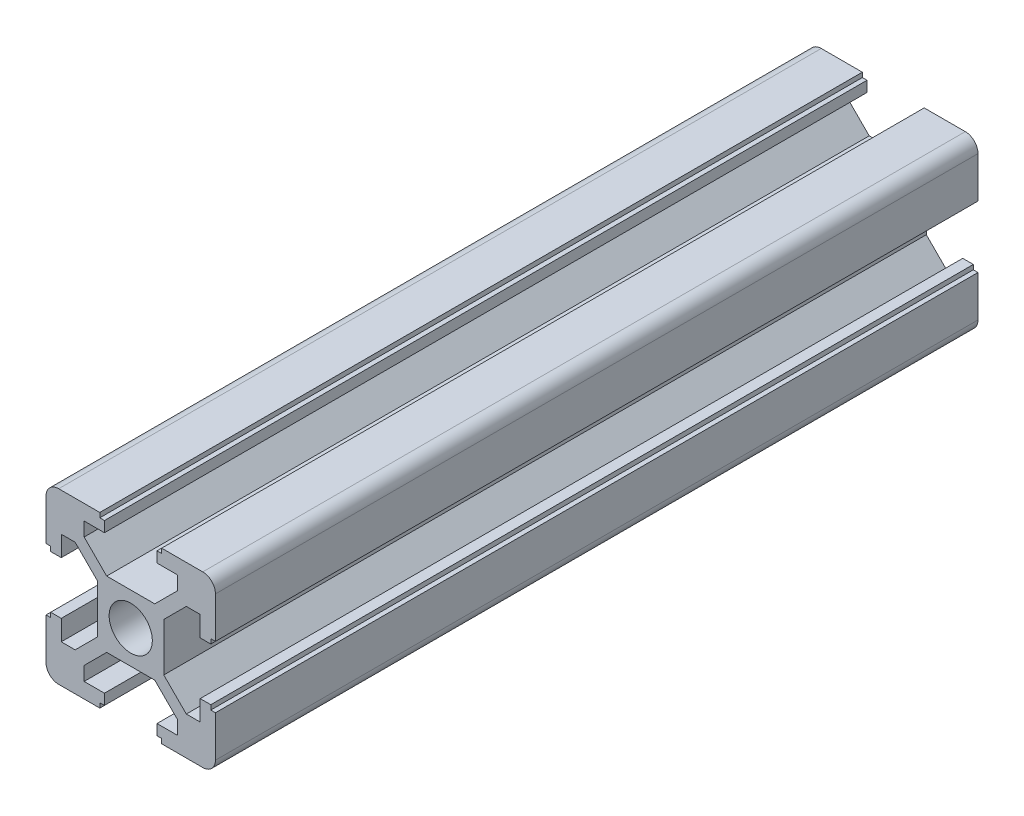
SolidWorks part; units mm, degrees
material "1060 Alloy"
ref_plane "Front Plane" through (0, 0, 0) normal (0, 0, 1) x (1, 0, 0)
ref_plane "Top Plane" through (0, 0, 0) normal (0, 1, 0) x (1, 0, 0)
ref_plane "Right Plane" through (0, 0, 0) normal (1, 0, 0) x (0, 0, -1)
sketch "Sketch2" plane through (0, 0, 0) normal (0, 0, 1) x (1, 0, 0)
  line L0 (-10, 10) -> (-3.65, 10)
  line L7 (-3.65, 10) -> (-3.65, 9.45)
  line L8 (-3.65, 9.45) -> (-3.1, 9.45)
  line L9 (-3.1, 9.45) -> (-3.1, 8.2)
  line L10 (-3.1, 8.2) -> (-5.5, 8.2)
  line L11 (-5.5, 8.2) -> (-5.5, 6.5607)
  line L18 (0, 0) -> (-10, 10) construction
  line L20 (-2.8393, 3.9) -> (-5.5, 6.5607)
  line L21 (-2.8393, 3.9) -> (0, 3.9)
  line L22 (-3.9, 2.8393) -> (-3.9, 0)
  line L23 (-3.9, 2.8393) -> (-6.5607, 5.5)
  line L24 (-8.2, 5.5) -> (-6.5607, 5.5)
  line L25 (-8.2, 3.1) -> (-8.2, 5.5)
  line L26 (-9.45, 3.1) -> (-8.2, 3.1)
  line L27 (-9.45, 3.65) -> (-9.45, 3.1)
  line L28 (-10, 3.65) -> (-9.45, 3.65)
  line L29 (-10, 10) -> (-10, 3.65)
  line L30 (2.8393, 3.9) -> (0, 3.9)
  line L31 (2.8393, 3.9) -> (5.5, 6.5607)
  line L32 (5.5, 8.2) -> (5.5, 6.5607)
  line L33 (3.1, 8.2) -> (5.5, 8.2)
  line L34 (3.1, 9.45) -> (3.1, 8.2)
  line L35 (3.65, 9.45) -> (3.1, 9.45)
  line L36 (10, 10) -> (3.65, 10)
  line L37 (10, 10) -> (10, 3.65)
  line L38 (10, 3.65) -> (9.45, 3.65)
  line L39 (9.45, 3.65) -> (9.45, 3.1)
  line L40 (9.45, 3.1) -> (8.2, 3.1)
  line L41 (8.2, 3.1) -> (8.2, 5.5)
  line L42 (8.2, 5.5) -> (6.5607, 5.5)
  line L43 (3.9, 2.8393) -> (6.5607, 5.5)
  line L44 (3.9, 2.8393) -> (3.9, 0)
  line L45 (3.65, 10) -> (3.65, 9.45)
  line L46 (3.9, -2.8393) -> (3.9, 0)
  line L47 (3.9, -2.8393) -> (6.5607, -5.5)
  line L48 (8.2, -5.5) -> (6.5607, -5.5)
  line L49 (8.2, -3.1) -> (8.2, -5.5)
  line L50 (9.45, -3.1) -> (8.2, -3.1)
  line L51 (9.45, -3.65) -> (9.45, -3.1)
  line L52 (10, -10) -> (10, -3.65)
  line L53 (10, -10) -> (3.65, -10)
  line L54 (3.65, -10) -> (3.65, -9.45)
  line L55 (3.65, -9.45) -> (3.1, -9.45)
  line L56 (3.1, -9.45) -> (3.1, -8.2)
  line L57 (3.1, -8.2) -> (5.5, -8.2)
  line L58 (5.5, -8.2) -> (5.5, -6.5607)
  line L59 (2.8393, -3.9) -> (5.5, -6.5607)
  line L60 (2.8393, -3.9) -> (0, -3.9)
  line L61 (10, -3.65) -> (9.45, -3.65)
  line L62 (-2.8393, -3.9) -> (0, -3.9)
  line L63 (-2.8393, -3.9) -> (-5.5, -6.5607)
  line L64 (-5.5, -8.2) -> (-5.5, -6.5607)
  line L65 (-3.1, -8.2) -> (-5.5, -8.2)
  line L66 (-3.1, -9.45) -> (-3.1, -8.2)
  line L67 (-3.65, -9.45) -> (-3.1, -9.45)
  line L68 (-10, -10) -> (-3.65, -10)
  line L69 (-10, -10) -> (-10, -3.65)
  line L70 (-10, -3.65) -> (-9.45, -3.65)
  line L71 (-9.45, -3.65) -> (-9.45, -3.1)
  line L72 (-9.45, -3.1) -> (-8.2, -3.1)
  line L73 (-8.2, -3.1) -> (-8.2, -5.5)
  line L74 (-8.2, -5.5) -> (-6.5607, -5.5)
  line L75 (-3.9, -2.8393) -> (-6.5607, -5.5)
  line L76 (-3.9, -2.8393) -> (-3.9, 0)
  line L77 (-3.65, -10) -> (-3.65, -9.45)
  dimension "D1" = 10
  dimension "D2" = 5.5
  dimension "D3" = 1.8
  dimension "D4" = 6.1
  dimension "D5" = 0.55
  dimension "D6" = 0.55
  dimension "D7" = 2.4
  dimension "D8" = 135
  dimension "D9" = 4
  dimension "D10" = 0.75
extrude "Boss-Extrude1" add sketch "Sketch2" against normal blind 90
sketch "Sketch3" plane through (0, 0, 0) normal (0, 0, 1) x (1, 0, 0)
  circle A0 centre (0, 0) radius 2.55
extrude "Cut-Extrude1" cut sketch "Sketch3" against normal through all contours A0
fillet "Fillet1" radius 1.5 4 edges at (-10, -10, -45) (10, -10, -45) (-10, 10, -45) (10, 10, -45)
